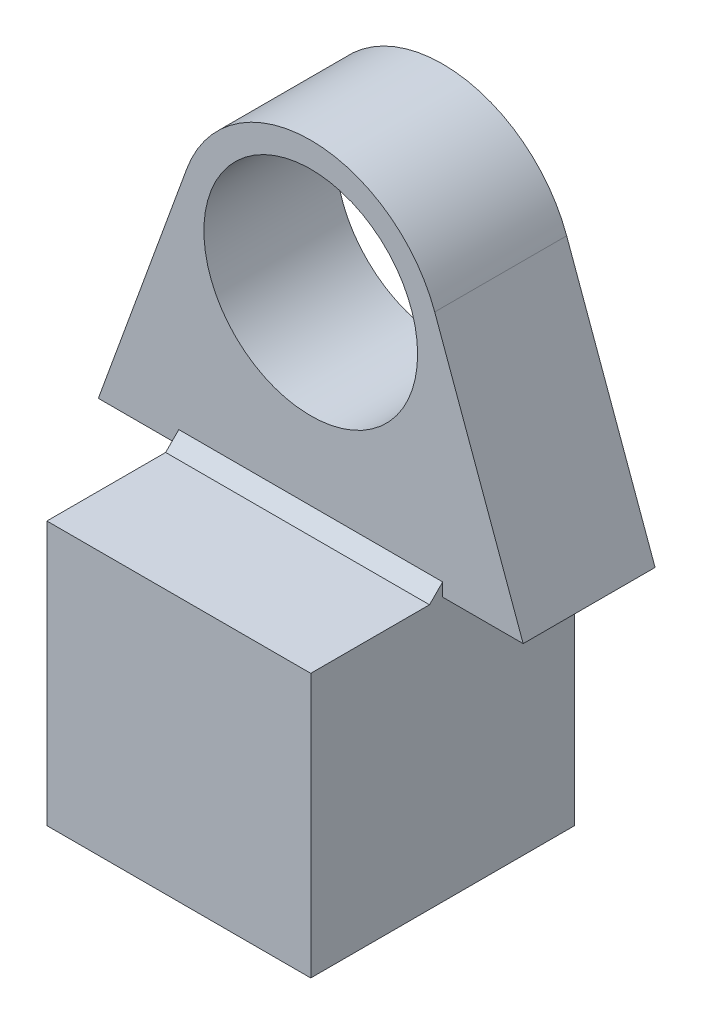
SolidWorks part; units mm, degrees
ref_plane "정면" through (0, 0, 0) normal (0, 0, 1) x (1, 0, 0)
ref_plane "윗면" through (0, 0, 0) normal (0, 1, 0) x (1, 0, 0)
ref_plane "우측면" through (0, 0, 0) normal (1, 0, 0) x (0, 0, -1)
sketch "스케치1" plane through (0, 0, 0) normal (0, 0, 1) x (1, 0, 0)
  line L0 (-16.1013, -15) -> (16.1013, -15)
  line L1 (-16.1013, -15) -> (-9.3969, 3.4202)
  line L2 (9.3969, 3.4202) -> (16.1013, -15)
  line L3 (-10.6418, 0) -> (10.6418, 0) construction
  line L5 (14.2815, -10) -> (-14.2815, -10) construction
  circle A0 centre (0, 0) radius 8.1
  circle A1 centre (0, 0) radius 10
  dimension "D1" = 16.2
  dimension "D2" = 20
  dimension "D3" = 5
  dimension "D4" = 70
  dimension "D5" = 70
extrude "보스-돌출1" add sketch "스케치1" against normal mid plane 20 contours A1 A0 | A1 L1 L0 L2
sketch "스케치2" plane through (0, 0, 0) normal (0, 0, 1) x (1, 0, 0)
  circle A0 centre (0, 0) radius 8.1
  circle A1 centre (0, 0) radius 8.1 construction
  circle A2 centre (0, 0) radius 6.6
  dimension "D1" = 1.5
extrude "보스-돌출2" add sketch "스케치2" along normal blind 10
sketch "스케치3" plane through (0, -15, 0) normal (0, -1, 0) x (1, 0, 0)
  line L0 (-16.1013, -10) -> (16.1013, -10) construction
  line L1 (10, -10) -> (-10, -10)
  line L2 (10, -10) -> (10, 10)
  line L3 (10, 10) -> (-10, 10)
  line L4 (-10, -10) -> (-10, 10)
  line L5 (-16.1013, 10) -> (16.1013, 10) construction
  point P8 (0, -10)
extrude "보스-돌출3" add sketch "스케치3" along normal blind 20
sketch "Sketch1" plane through (0, 0, 10) normal (0, 0, 1) x (1, 0, 0)
  line L1 (-16.1013, -15) -> (16.1013, -15)
  line L2 (-16.1013, -15) -> (-16.1013, 10)
  line L3 (-16.1013, 10) -> (16.1013, 10)
  line L4 (16.1013, -15) -> (16.1013, 10)
  arc A0 (9.3969, 3.4202) -> (-9.3969, 3.4202) centre (0, 0) ccw construction
  point P5 (0, 0)
extrude "Extrude1" cut sketch "Sketch1" against normal up to surface (10 mm away) up to face at (8.1, 0, 0)
chamfer "Chamfer1" distance 1 angle 45 1 edges at (0, -15, 0)
